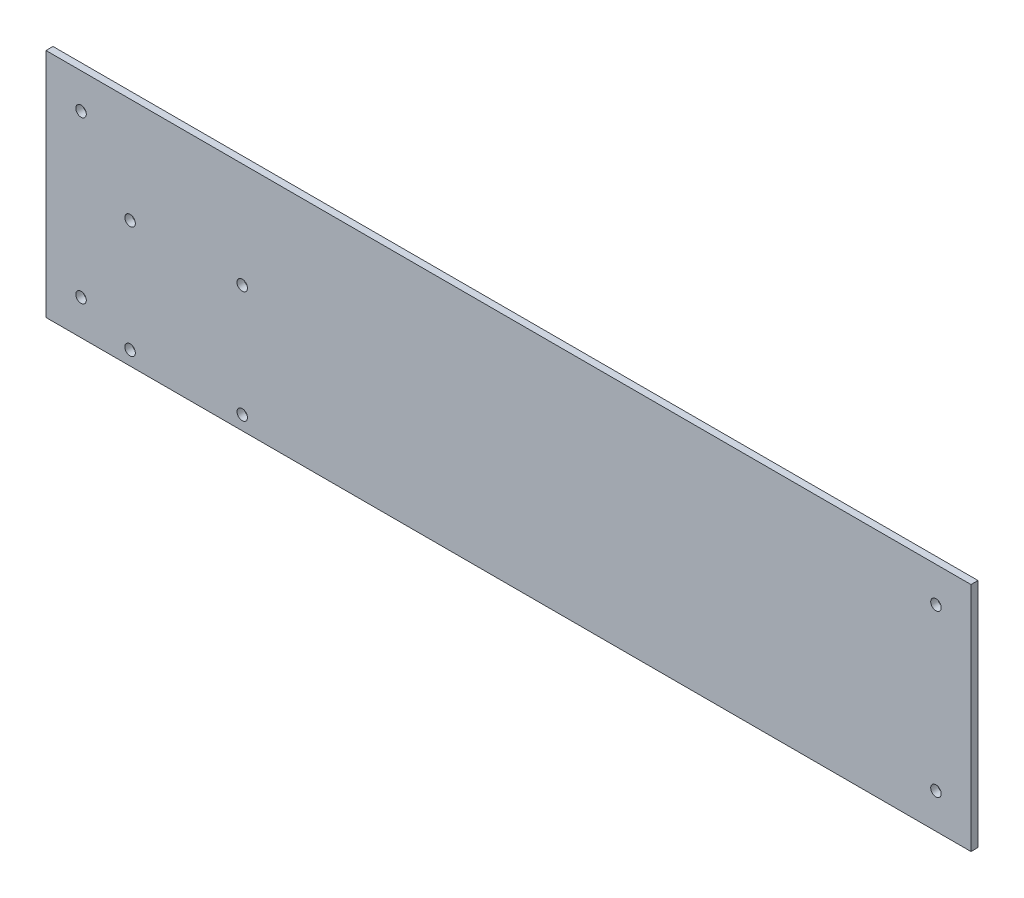
SolidWorks part; units mm, degrees
ref_plane "Plan de face" through (0, 0, 0) normal (0, 0, 1) x (1, 0, 0)
ref_plane "Plan de dessus" through (0, 0, 0) normal (0, 1, 0) x (1, 0, 0)
ref_plane "Plan de droite" through (0, 0, 0) normal (1, 0, 0) x (0, 0, -1)
sketch "Esquisse1" plane through (0, 0, 0) normal (0, 0, 1) x (1, 0, 0)
  line L1 (-45.7387, 52.9082) -> (218.2613, 52.9082)
  line L2 (-45.7387, 52.9082) -> (-45.7387, -13.0918)
  line L3 (-45.7387, -13.0918) -> (218.2613, -13.0918)
  line L4 (218.2613, 52.9082) -> (218.2613, -13.0918)
  circle A0 centre (-35.7387, 42.9082) radius 1.5
  circle A1 centre (-35.7387, -3.0918) radius 1.5
  circle A2 centre (208.2613, 42.9082) radius 1.5
  circle A3 centre (208.2613, -3.0918) radius 1.5
  dimension "D3" = 10
  dimension "D5" = 10
  dimension "D7" = 10
  dimension "D1" = 66
  dimension "D2" = 264
  dimension "D4" = 10
  dimension "D6" = 10
  dimension "D8" = 10
  dimension "D9" = 10
  dimension "D10" = 10
extrude "Extrusion1" add sketch "Esquisse1" along normal blind 2
sketch "Esquisse2" plane through (0, 0, 2) normal (0, 0, 1) x (1, 0, 0)
  line L1 (-21.7387, 22.9082) -> (10.2613, 22.9082) construction
  line L2 (-21.7387, 22.9082) -> (-21.7387, -9.0918) construction
  line L3 (-21.7387, -9.0918) -> (10.2613, -9.0918) construction
  line L4 (10.2613, 22.9082) -> (10.2613, -9.0918) construction
  line L5 (-45.7387, -13.0918) -> (218.2613, -13.0918) construction
  line L6 (-45.7387, 52.9082) -> (-45.7387, -13.0918) construction
  circle A0 centre (-21.7387, 22.9082) radius 1.5
  circle A1 centre (10.2613, 22.9082) radius 1.5
  circle A2 centre (10.2613, -9.0918) radius 1.5
  circle A3 centre (-21.7387, -9.0918) radius 1.5
  dimension "D3" = 4
  dimension "D1" = 32
  dimension "D2" = 32
  dimension "D4" = 24
extrude "Extrusion2" cut sketch "Esquisse2" against normal blind 10
